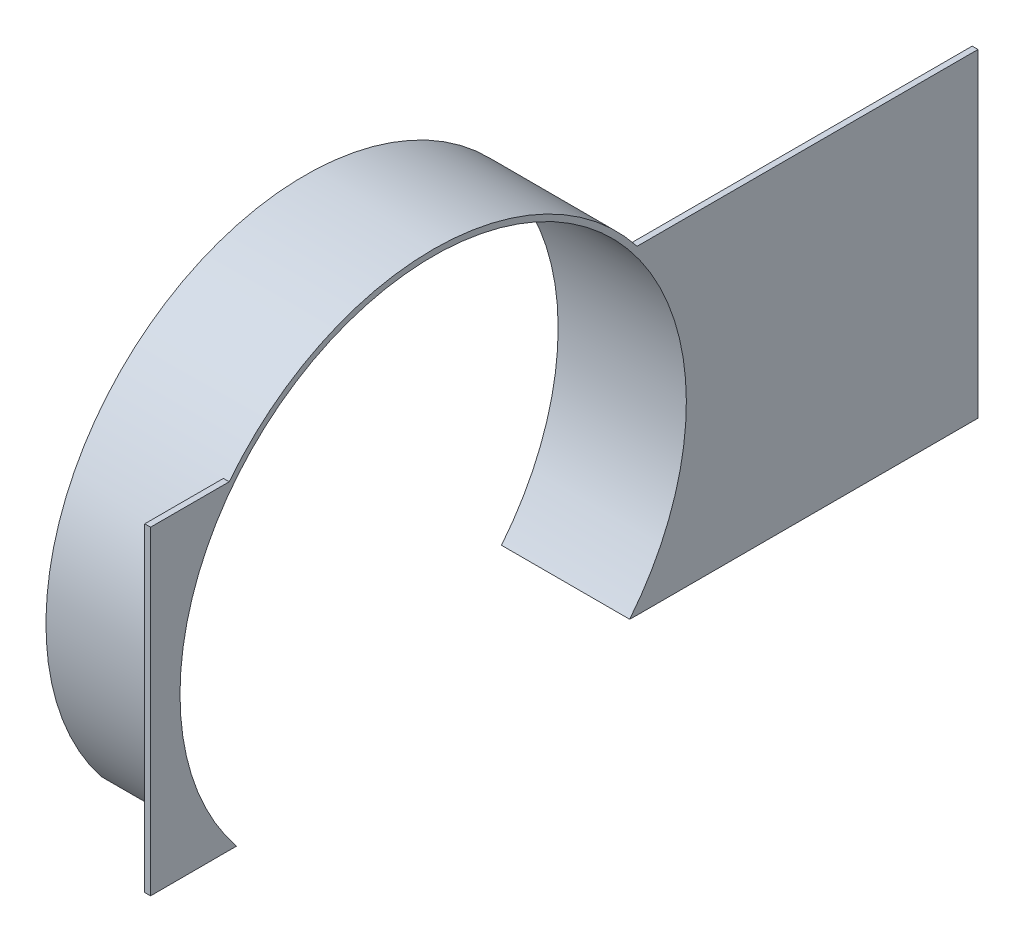
SolidWorks part; units mm, degrees
ref_plane "Front Plane" through (0, 0, 0) normal (0, 0, 1) x (1, 0, 0)
ref_plane "Top Plane" through (0, 0, 0) normal (0, 1, 0) x (1, 0, 0)
ref_plane "Right Plane" through (0, 0, 0) normal (1, 0, 0) x (0, 0, -1)
sketch "Sketch1" plane through (0, 0, 0) normal (1, 0, 0) x (0, 0, -1)
  line L2 (-95.034, 0.0447) -> (-92.4435, 0.0033)
  line L3 (42.4459, 0) -> (45.004, 0)
  arc A3 (-95.034, 0.0447) -> (45.004, 0) centre (-24.9975, 54.7996) cw
  arc A4 (-92.4435, 0.0033) -> (42.4459, 0) centre (-24.9975, 54.7996) cw
  dimension "D1" = 88.9
  dimension "D2" = 2
sketch "Sketch2" plane through (0, 0, 0) normal (1, 0, 0) x (0, 0, -1)
  line L0 (-120, 0) -> (-95.034, 0.0447)
  line L1 (-120, 109.6) -> (-122, 109.6)
  line L2 (-120, 109.6) -> (-94.9984, 109.6)
  line L3 (50, 109.6) -> (45.0035, 109.6)
  line L5 (160, 109.6) -> (50, 109.6)
  line L7 (-122, 109.6) -> (-122, 0)
  line L9 (-122, 0) -> (-120, 0)
  line L10 (160, 0) -> (162, 0)
  line L12 (162, 0) -> (162, 109.6)
  line L14 (162, 109.6) -> (160, 109.6)
  line L15 (44.965, -0.0498) -> (160, 0)
  line L16 (-92.4435, 0.0033) -> (-95.034, 0.0447)
  line L18 (42.4459, 0) -> (44.965, -0.0498)
  arc A1 (-92.4435, 0.0033) -> (42.4459, 0) centre (-24.9975, 54.7996) cw
  arc A2 (-95.034, 0.0447) -> (44.965, -0.0498) centre (-24.9975, 54.7996) cw
  arc A3 (42.4459, 0) -> (-92.4435, 0.0033) centre (-24.9975, 54.7996) ccw construction
  dimension "D2" = 2
  dimension "D1" = 2
  dimension "D3" = 109.6
  dimension "D4" = 115.035
extrude "Boss-Extrude1" add sketch "Sketch1" against normal blind 42
extrude "Boss-Extrude4" add sketch "Sketch2" along normal blind 2 contours L0 A2 L2 L1 L7 L9 | A2 L16 A1 L18 | L3 A2 L15 L10 L12 L14 L5
sketch3d "3DSketch1"
  point P0 (0, 71.8249, -83.4498)
equation "\"gap\"= 1mm"
equation "\"casewidth\"= 2mm"
equation "\"D2@Sketch1\"=\"casewidth\""
equation "\"D1@Sketch2\"=\"casewidth\""
equation "\"D2@Sketch2\"=\"casewidth\""
equation "\"D1@Boss-Extrude4\"=\"casewidth\""
